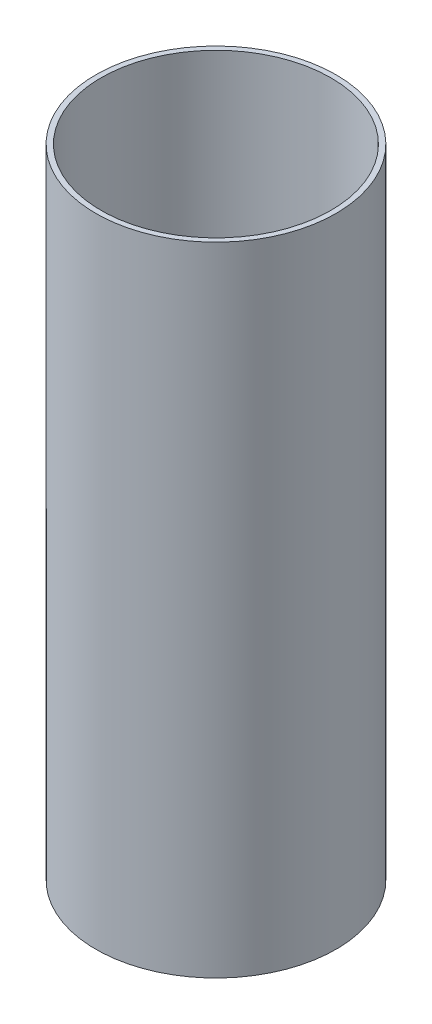
SolidWorks part; units mm, degrees
material "1023 碳钢板 (SS)"
ref_plane "前视基准面" through (0, 0, 0) normal (0, 0, 1) x (1, 0, 0)
ref_plane "上视基准面" through (0, 0, 0) normal (0, 1, 0) x (1, 0, 0)
ref_plane "右视基准面" through (0, 0, 0) normal (1, 0, 0) x (0, 0, -1)
sketch "草图1" plane through (0, 0, 0) normal (0, 1, 0) x (1, 0, 0)
  circle A0 centre (0, -141) radius 11.5
  dimension "D1" = 23
  dimension "D2" = 141
extrude "凸台-拉伸1" add sketch "草图1" along normal blind 61 from offset 69.25
sketch "草图2" plane through (0, 0, 0) normal (0, 1, 0) x (1, 0, 0)
  circle A0 centre (0, -141) radius 11
  dimension "D1" = 22
extrude "切除-拉伸1" cut sketch "草图2" along normal blind 61 from offset 69.25
